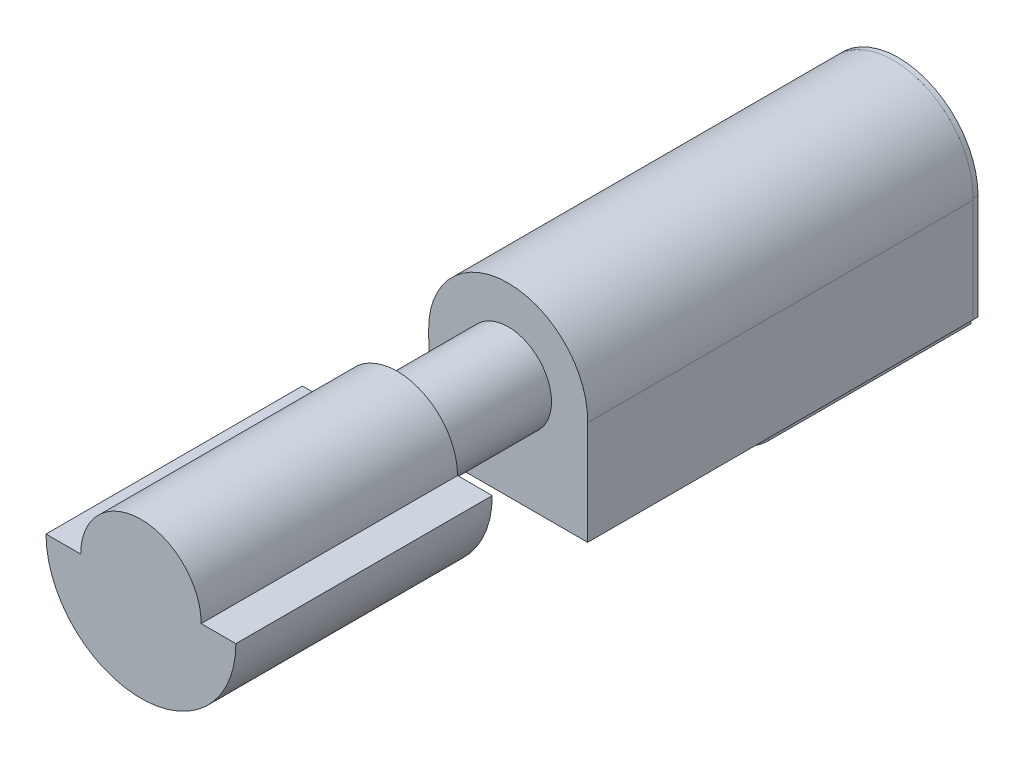
SolidWorks part; units mm, degrees
material "1.4000 (X6Cr13)"
ref_plane "Plan de face" through (0, 0, 0) normal (0, 0, 1) x (1, 0, 0)
ref_plane "Plan de dessus" through (0, 0, 0) normal (0, 1, 0) x (1, 0, 0)
ref_plane "Plan de droite" through (0, 0, 0) normal (1, 0, 0) x (0, 0, -1)
sketch "Esquisse1" plane through (0, 0, 0) normal (0, 0, 1) x (1, 0, 0)
  circle A0 centre (0, 0) radius 1.65
extrude "Boss.-Extru.1" add sketch "Esquisse1" along normal blind 8
sketch "Esquisse2" plane through (0, 0, 0) normal (0, 0, -1) x (-1, 0, 0)
  line L0 (0, 1.65) -> (0, -2.1505) construction
  line L1 (-1.6, -2.1505) -> (1.6, -2.1505) construction
  line L3 (-1.6, -2.1505) -> (1.6, -2.1505)
  line L4 (-1.6, -2.1505) -> (-1.6, 0.1276)
  line L5 (-1.6, 0.1276) -> (1.6, 0.1276)
  line L6 (1.6, -2.1505) -> (1.6, 0.1276)
  circle A0 centre (0, 0) radius 1.65 construction
  dimension "D1" = 1.6
extrude "Boss.-Extru.2" add sketch "Esquisse2" against normal blind 4.2
sketch "Esquisse3" plane through (0, 0, 8) normal (0, 0, 1) x (1, 0, 0)
  circle A0 centre (0, 0) radius 0.9
extrude "Boss.-Extru.3" add sketch "Esquisse3" along normal blind 2.3
sketch "Esquisse4" plane through (0, 0, 10.3) normal (0, 0, 1) x (1, 0, 0)
  circle A0 centre (0, 0) radius 1.97
extrude "Boss.-Extru.4" add sketch "Esquisse4" along normal blind 5.32
sketch "Esquisse5" plane through (0, 0, 15.62) normal (0, 0, 1) x (1, 0, 0)
  line L0 (-1.25, 0) -> (-1.97, 0)
  line L1 (1.25, 0) -> (1.97, 0)
  arc A0 (1.25, 0) -> (-1.25, 0) centre (0, 0) ccw
  circle A1 centre (0, 0) radius 1.97 construction
  arc A2 (-1.97, 0) -> (1.97, 0) centre (0, 0) ccw
sketch "Esquisse6" plane through (0, 0, 15.62) normal (0, 0, 1) x (1, 0, 0)
  line L0 (-1.97, 0) -> (-1.25, 0)
  line L1 (1.25, 0) -> (1.97, 0)
  arc A0 (-1.25, 0) -> (1.25, 0) centre (0, 0) cw
  arc A1 (-1.97, 0) -> (1.97, 0) centre (0, 0) cw
extrude "Enlèv. mat.-Extru.2" cut sketch "Esquisse6" against normal blind 5.32
sketch "Esquisse7" plane through (0, -2.1505, 0) normal (0, -1, 0) x (1, 0, 0)
  line L0 (0, 0) -> (0, -0.6426) construction
  line L1 (1.6, 0) -> (0.3, 0)
  line L2 (1.6, 0) -> (1.6, 4.2)
  line L3 (1.1, 4.7) -> (0.8, 4.7)
  line L4 (0.3, 0) -> (0.3, 4.2)
  line L5 (-1.6, 0) -> (-0.3, 0)
  line L6 (-1.6, 0) -> (-1.6, 4.2)
  line L7 (-1.1, 4.7) -> (-0.8, 4.7)
  line L8 (-0.3, 0) -> (-0.3, 4.2)
  arc A0 (1.6, 4.2) -> (1.1, 4.7) centre (1.1, 4.2) ccw
  arc A1 (0.8, 4.7) -> (0.3, 4.2) centre (0.8, 4.2) ccw
  arc A2 (-1.6, 4.2) -> (-1.1, 4.7) centre (-1.1, 4.2) cw
  arc A3 (-0.8, 4.7) -> (-0.3, 4.2) centre (-0.8, 4.2) cw
  point P14 (1.6, 4.7)
  point P17 (0.3, 4.7)
  point P20 (-1.6, 4.7)
  point P23 (-0.3, 4.7)
  dimension "D3" = 0.5
  dimension "D1" = 1.3
  dimension "D2" = 4.7
extrude "Boss.-Extru.5" add sketch "Esquisse7" along normal blind 0.1
sketch "Esquisse8" plane through (0, 0, 0) normal (0, 0, -1) x (-1, 0, 0)
  line L0 (-1.25, 0) -> (-1.97, 0) construction
  line L2 (-1.65, 0) -> (-1.65, -2.1505)
  line L3 (-1.65, -2.1505) -> (1.6, -2.1505)
  line L5 (1.25, 0) -> (1.97, 0) construction
  line L7 (1.61, -2.1505) -> (1.6, -2.1505)
  line L8 (1.61, -2.1505) -> (1.65, 0)
  arc A0 (1.6, -0.4031) -> (-1.6, -0.4031) centre (0, 0) ccw construction
  arc A1 (-1.65, 0) -> (1.65, 0) centre (0, 0.0361) cw
extrude "Boss.-Extru.6" add sketch "Esquisse8" against normal up to surface (8 mm away) up to face at (0.9, 0, 8)
sketch "Esquisse9" plane through (0, 0, 0) normal (0, 0, -1) x (-1, 0, 0)
  line L0 (-1.25, 0) -> (-1.25, -2.1505)
  line L1 (-1.25, -2.1505) -> (-1.65, -2.1505)
  line L2 (-1.65, -2.1505) -> (-1.6504, 0.0361)
  line L3 (1.65, 0) -> (1.6, -2.1505)
  line L4 (1.6, -2.1505) -> (1.25, -2.1505)
  line L5 (1.25, -2.1505) -> (1.25, 0)
  arc A0 (1.25, 0) -> (-1.25, 0) centre (0, 0) ccw
  arc A1 (1.65, 0) -> (-1.65, 0) centre (0, 0.0361) ccw construction
  arc A2 (-1.6504, 0.0361) -> (1.65, 0) centre (0, 0.0364) cw
extrude "Boss.-Extru.7" add sketch "Esquisse9" along normal blind 0.1
